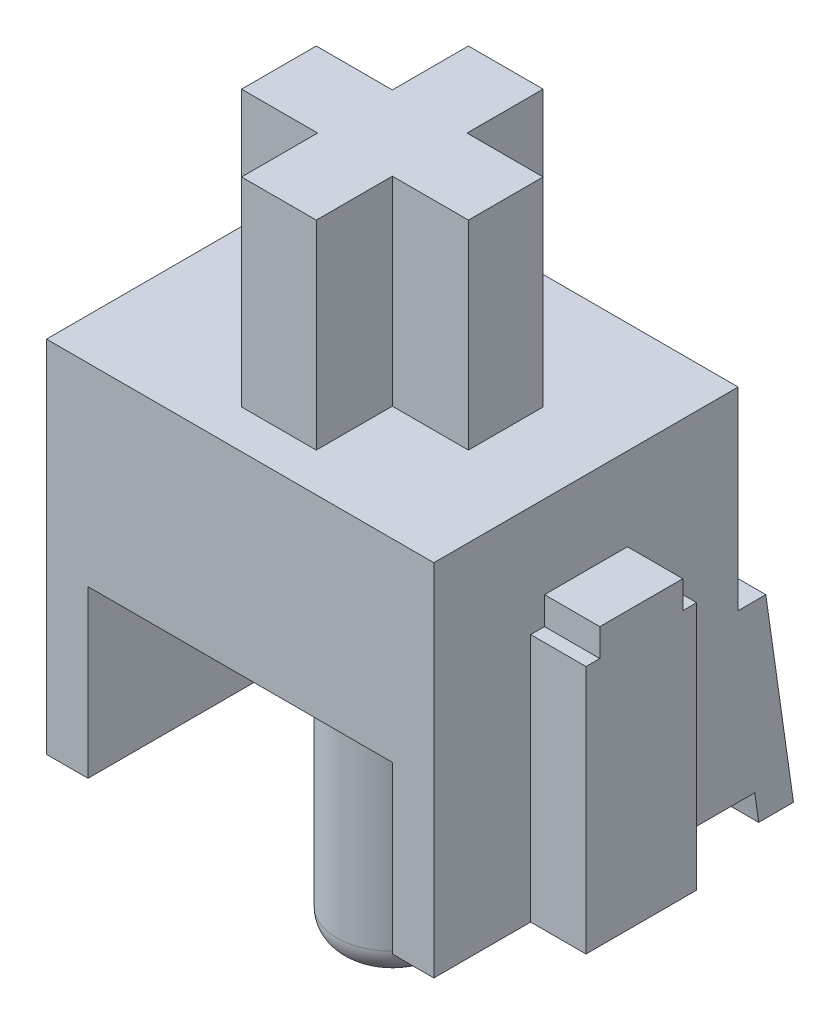
SolidWorks part; units mm, degrees
ref_plane "Front Plane" through (0, 0, 0) normal (0, 0, 1) x (1, 0, 0)
ref_plane "Top Plane" through (0, 0, 0) normal (0, 1, 0) x (1, 0, 0)
ref_plane "Right Plane" through (0, 0, 0) normal (1, 0, 0) x (0, 0, -1)
sketch "Sketch1" plane through (0, 0, 0) normal (0, 1, 0) x (1, 0, 0)
  line L1 (-3.5, 2.75) -> (3.5, 2.75)
  line L2 (-3.5, 2.75) -> (-3.5, -2.75)
  line L3 (-3.5, -2.75) -> (3.5, -2.75)
  line L4 (3.5, 2.75) -> (3.5, -2.75)
  line L5 (-3.5, 2.75) -> (3.5, -2.75) construction
  line L6 (-3.5, -2.75) -> (3.5, 2.75) construction
  point P0 (0, 0)
  dimension "D1" = 5.5
  dimension "D2" = 7
extrude "Boss-Extrude1" add sketch "Sketch1" along normal blind 6.5
sketch "Sketch4" plane through (0, 0, 2.75) normal (0, 0, 1) x (1, 0, 0)
  line L1 (-3.5, 0) -> (3.5, 0) construction
  line L3 (-2.75, 0) -> (2.75, 0)
  line L4 (-2.75, 0) -> (-2.75, 3)
  line L5 (-2.75, 3) -> (2.75, 3)
  line L6 (2.75, 0) -> (2.75, 3)
  dimension "D2" = 5.5
  dimension "D3" = 3
extrude "Cut-Extrude1" cut sketch "Sketch4" against normal through all
sketch "Sketch6" plane through (-3.5, 0, 0) normal (-1, 0, 0) x (0, 0, 1)
  line L1 (-2.75, 0) -> (2.75, 0) construction
  line L2 (-1, 4.5) -> (-0.75, 4.5)
  line L3 (-1, 0) -> (1, 0)
  line L4 (-1, 0) -> (-1, 4.5)
  line L6 (1, 0) -> (1, 4.5)
  line L7 (-0.75, 4.5) -> (-0.75, 5)
  line L8 (-0.75, 5) -> (0.75, 5)
  line L9 (0.75, 5) -> (0.75, 4.5)
  line L10 (0.75, 4.5) -> (1, 4.5)
  dimension "D2" = 4.5
  dimension "D3" = 2
  dimension "D4" = 4.5
  dimension "D5" = 0.25
  dimension "D6" = 0.5
  dimension "D7" = 1.5
  dimension "D8" = 0.5
extrude "Boss-Extrude2" add sketch "Sketch6" along normal blind 1
sketch "Sketch7" plane through (3.5, 0, 0) normal (1, 0, 0) x (0, 0, -1)
  line L1 (-2.75, 0) -> (2.75, 0) construction
  line L2 (-1, 0) -> (-1, 4.5)
  line L3 (-1, 4.5) -> (-0.75, 4.5)
  line L4 (-0.75, 4.5) -> (-0.75, 5)
  line L5 (-0.75, 5) -> (0.75, 5)
  line L6 (0.75, 5) -> (0.75, 4.5)
  line L7 (0.75, 4.5) -> (1, 4.5)
  line L9 (1, 4.5) -> (1, 0)
  line L10 (1, 0) -> (-1, 0)
  dimension "D2" = 4.5
  dimension "D3" = 0.25
  dimension "D4" = 1.5
  dimension "D5" = 0.5
  dimension "D6" = 0.25
  dimension "D7" = 0.5
extrude "Boss-Extrude3" add sketch "Sketch7" along normal blind 1
sketch "Sketch8" plane through (0, 3, 0) normal (0, -1, 0) x (1, 0, 0)
  circle A0 centre (0, 0) radius 2.25
  dimension "D1" = 4.5
extrude "Cut-Extrude2" cut sketch "Sketch8" against normal blind 2
sketch "Sketch10" plane through (0, 6.5, 0) normal (0, 1, 0) x (1, 0, 0)
  line L0 (-2.05, -0.675) -> (-2.05, 0.675)
  line L11 (2.05, -0.675) -> (0.675, -0.675)
  line L12 (0.675, -2.05) -> (0.675, -0.675)
  line L15 (-2.05, -0.675) -> (-0.675, -0.675)
  line L16 (-0.675, -2.05) -> (-0.675, -0.675)
  line L19 (-2.05, 0.675) -> (-0.675, 0.675)
  line L20 (-0.675, 2.05) -> (-0.675, 0.675)
  line L23 (2.05, 0.675) -> (0.675, 0.675)
  line L24 (0.675, 2.05) -> (0.675, 0.675)
  line L25 (-0.675, -2.05) -> (0.675, -2.05)
  line L26 (2.05, 0.675) -> (2.05, -0.675)
  line L27 (0.675, 2.05) -> (-0.675, 2.05)
  point P1 (2.05, 0)
  point P4 (0, 2.05)
  dimension "D1" = 1.35
  dimension "D2" = 1.35
  dimension "D3" = 1.375
  dimension "D4" = 1.35
  dimension "D5" = 1.375
  dimension "D6" = 1.375
  dimension "D7" = 1.35
  dimension "D8" = 1.375
  dimension "D9" = 0
  dimension "D10" = 0
  dimension "D11" = 1.375
  dimension "D12" = 1.375
extrude "Boss-Extrude4" add sketch "Sketch10" along normal blind 3.6
sketch "Sketch11" plane through (0, 5, 0) normal (0, -1, 0) x (1, 0, 0)
  circle A0 centre (0, 0) radius 1
  dimension "D1" = 2
extrude "Boss-Extrude5" add sketch "Sketch11" along normal blind 7.5
fillet "Fillet1" radius 0.5 1 edges at (0, -2.5, -1)
sketch "Sketch12" plane through (0, 0, -2.75) normal (0, 0, -1) x (-1, 0, 0)
  line L1 (-3.5, 0) -> (-2.75, 0)
  line L2 (-3.5, 0) -> (-3.5, 3)
  line L3 (-3.5, 3) -> (-2.75, 3)
  line L4 (-2.75, 0) -> (-2.75, 3)
  line L5 (2.75, 3) -> (3.5, 3)
  line L6 (2.75, 3) -> (2.75, 0)
  line L7 (2.75, 0) -> (3.5, 0)
  line L8 (3.5, 3) -> (3.5, 0)
extrude "Boss-Extrude6" add sketch "Sketch12" along normal blind 1
sketch "Sketch14" plane through (0, 0, 0) normal (0, -1, 0) x (1, 0, 0)
  line L0 (-2.75, -3.75) -> (-2.75, 2.75) construction
  line L1 (-3.5, -3.75) -> (-2.75, -3.75)
  line L2 (-3.5, -3.75) -> (-3.5, -2.75)
  line L3 (-3.5, -2.75) -> (-2.75, -2.75)
  line L4 (-2.75, -3.75) -> (-2.75, -2.75)
  line L5 (2.75, -3.75) -> (2.75, 2.75) construction
  line L6 (3.5, -3.75) -> (2.75, -3.75)
  line L7 (3.5, -3.75) -> (3.5, -2.75)
  line L8 (3.5, -2.75) -> (2.75, -2.75)
  line L9 (2.75, -3.75) -> (2.75, -2.75)
  line L10 (2.75, -3.75) -> (2.75, -2.75) construction
  dimension "D1" = 1
extrude "Boss-Extrude7" add sketch "Sketch14" along normal blind 0.5
sketch "Sketch15" plane through (3.5, 0, 0) normal (1, 0, 0) x (0, 0, -1)
  line L0 (3.75, 3) -> (3.25, 3)
  line L1 (3.75, 3) -> (2.75, 3) construction
  line L2 (3.25, 3) -> (3.75, -0.5)
  line L3 (2.75, 0) -> (3.05, 0)
  line L4 (3.05, 0) -> (3.1214, -0.5)
  line L5 (3.75, -0.5) -> (2.75, -0.5) construction
  line L6 (3.1214, -0.5) -> (2.75, -0.5)
  line L7 (2.75, -0.5) -> (2.75, 0)
  line L8 (3.75, 3) -> (3.75, -0.5)
  dimension "D1" = 0.5
  dimension "D2" = 0.3
extrude "Cut-Extrude3" cut sketch "Sketch15" against normal through all both and the other way through all
